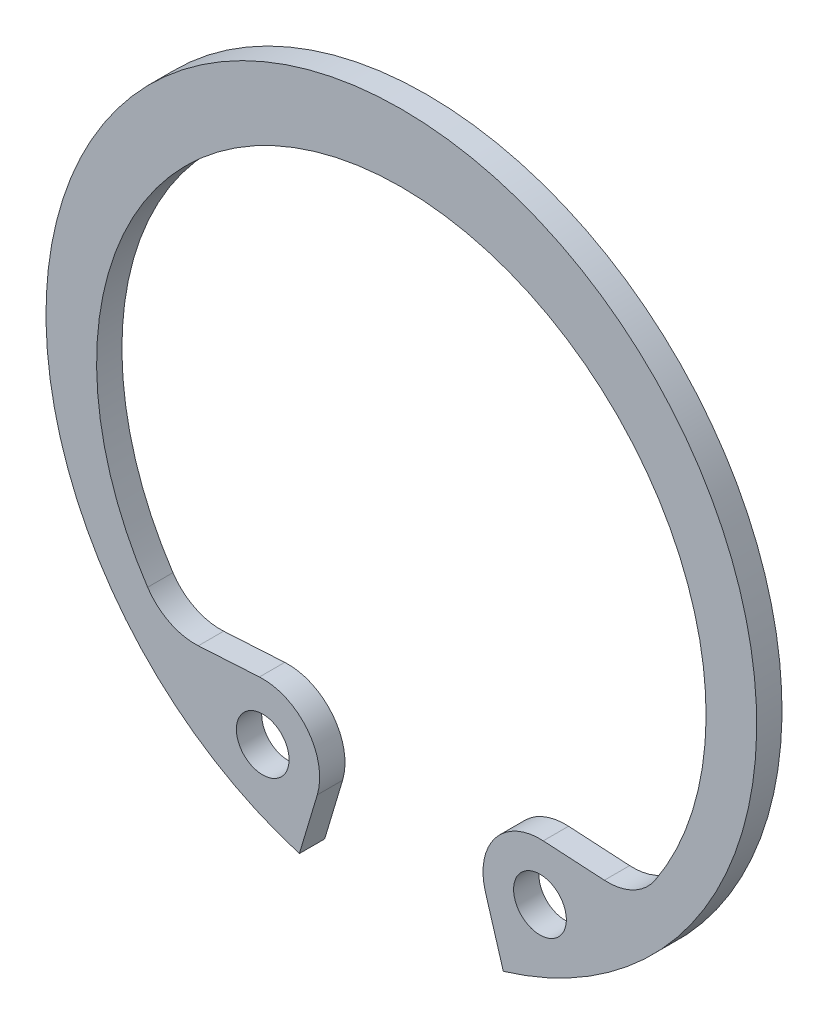
SolidWorks part; units mm, degrees
ref_plane "Face" through (0, 0, 0) normal (0, 0, 1) x (1, 0, 0)
ref_plane "Dessus" through (0, 0, 0) normal (0, 1, 0) x (1, 0, 0)
ref_plane "Droite" through (0, 0, 0) normal (1, 0, 0) x (0, 0, -1)
sketch "Esquisse1" plane through (0, 0, 0) normal (0, 0, 1) x (1, 0, 0)
  line L0 (0, 13.65) -> (0, 16.85) construction
  line L1 (3.986, -13.3058) -> (4.8354, -16.1413)
  line L2 (5.3183, -10.1399) -> (7.8265, -14.9221) construction
  line L3 (9.6263, -10.0038) -> (6.729, -9.8355)
  line L4 (-9.6263, -10.0038) -> (-6.729, -9.8355)
  line L5 (-3.986, -13.3058) -> (-4.8354, -16.1413)
  line L6 (4.8704, -13.3812) -> (5.8827, -16.1627) construction
  line L7 (-4.8704, -13.3812) -> (-5.8827, -16.1627) construction
  arc A0 (4.8354, -16.1413) -> (-4.8354, -16.1413) centre (0, 0) ccw
  arc A1 (12.0308, -8.8038) -> (-12.0308, -8.8038) centre (0, -0.8) ccw
  arc A2 (6.729, -9.8355) -> (3.986, -13.3058) centre (6.5724, -12.531) ccw
  arc A3 (9.6263, -10.0038) -> (12.0308, -8.8038) centre (9.7829, -7.3083) ccw
  circle A4 centre (6.5724, -12.531) radius 1.25
  arc A5 (-9.6263, -10.0038) -> (-12.0308, -8.8038) centre (-9.7829, -7.3083) cw
  circle A6 centre (-6.5724, -12.531) radius 1.25
  arc A7 (-6.729, -9.8355) -> (-3.986, -13.3058) centre (-6.5724, -12.531) cw
  arc A8 (5.8827, -16.1627) -> (-5.8827, -16.1627) centre (0, 0) ccw construction
  circle A9 centre (0, 0) radius 16 construction
  dimension "dext" = 34.4
extrude "Base-Extrusion" add sketch "Esquisse1" along normal blind 1.2
sketch "Esquisse2" plane through (0, 0, 0) normal (1, 0, 0) x (0, 0, -1)
  line L0 (-1.2, 16.85) -> (-1.2, 13.65)
  line L1 (-1.2, 16.85) -> (-1.2, 13.65)
  line L2 (-1.2, 16.85) -> (0, 16.85)
  line L3 (-1.2, 16.85) -> (0, 16.85)
  line L4 (0, 16.85) -> (0, 13.65)
  line L5 (0, 16.85) -> (0, 13.65)
equation "\"D3@Esquisse1\" = \"b@Esquisse1\"/4"
equation "\"D7@Esquisse1\" = 360-(360-\"D9@Esquisse1\")*\"dext@Esquisse1\"/\"dgorge@Esquisse1\""
